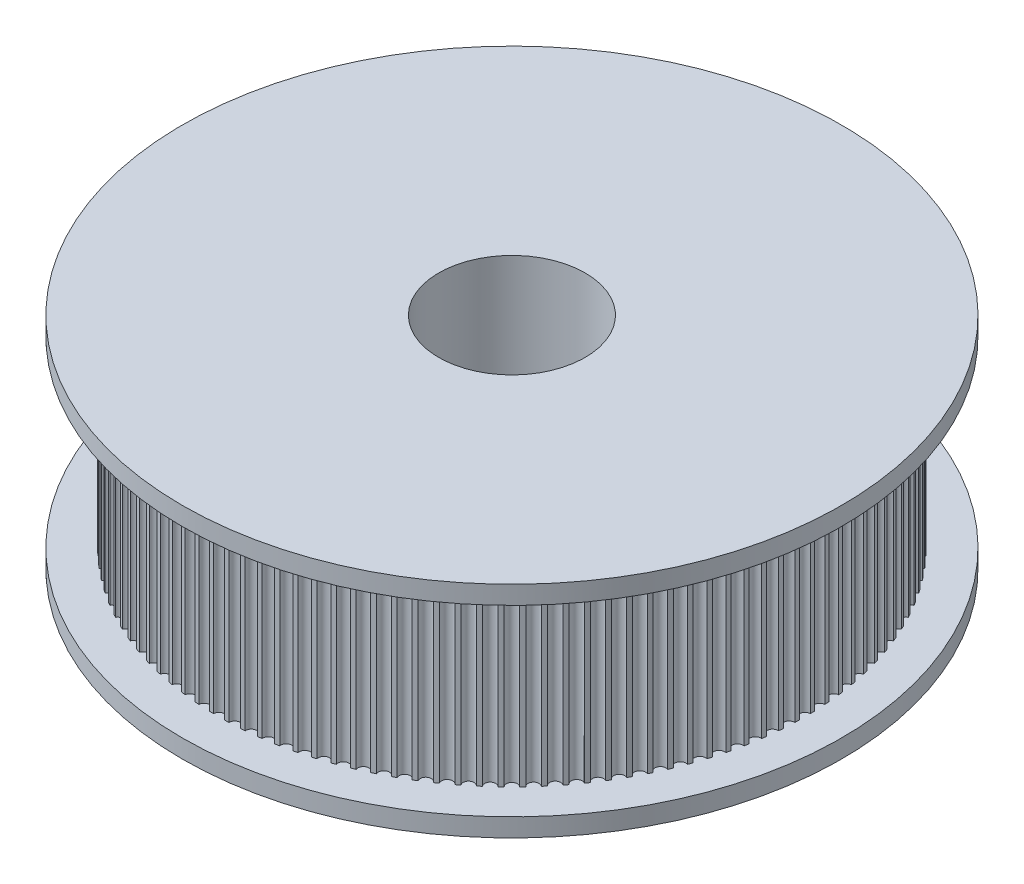
SolidWorks part; units mm, degrees
ref_plane "Front Plane" through (0, 0, 0) normal (0, 0, 1) x (1, 0, 0)
ref_plane "Top Plane" through (0, 0, 0) normal (0, 1, 0) x (1, 0, 0)
ref_plane "Right Plane" through (0, 0, 0) normal (1, 0, 0) x (0, 0, -1)
sketch "Sketch2" plane through (0, 0, 0) normal (0, 0, 1) x (1, 0, 0)
  line L0 (0, 54.4245) -> (0, -51.2809) construction
  line L1 (0, 0.9127) -> (18, 0.9127)
  line L2 (18, 0.9127) -> (18, -0.0873)
  line L3 (18, -0.0873) -> (16, -0.0873)
  line L4 (16, -0.0873) -> (16, -10.0873)
  line L5 (16, -10.0873) -> (18, -10.0873)
  line L6 (18, -10.0873) -> (18, -11.0873)
  line L7 (18, -11.0873) -> (0, -11.0873)
  line L8 (0, 0.9127) -> (0, -11.0873)
  dimension "D1" = 18
  dimension "D2" = 2
  dimension "D3" = 18
  dimension "D4" = 12
  dimension "D5" = 1
  dimension "D6" = 1
revolve "Revolve1" add sketch "Sketch2" angle 360 about L0
sketch "Sketch3" plane through (0, -11.0873, 0) normal (0, -1, 0) x (-1, 0, 0)
  circle A0 centre (0, 0) radius 4
extrude "Cut-Extrude1" cut sketch "Sketch3" against normal blind 29
sketch "Sketch4" plane through (0, -10.0873, 0) normal (0, 1, 0) x (1, 0, 0)
  line L0 (0, 18) -> (0, -4) construction
  circle A0 centre (0, 0) radius 18 construction
  circle A1 centre (0, 0) radius 4 construction
  circle A2 centre (0, 0) radius 16 construction
  circle A3 centre (0, 0) radius 16
  circle A4 centre (0, 16) radius 0.3
extrude "Cut-Extrude2" cut sketch "Sketch4" along normal blind 10 contours A4
pattern_circular "CirPattern1" count 120 every 3 about axis through (0, 0, 0) along (0, 1, 0) of "Cut-Extrude2"
